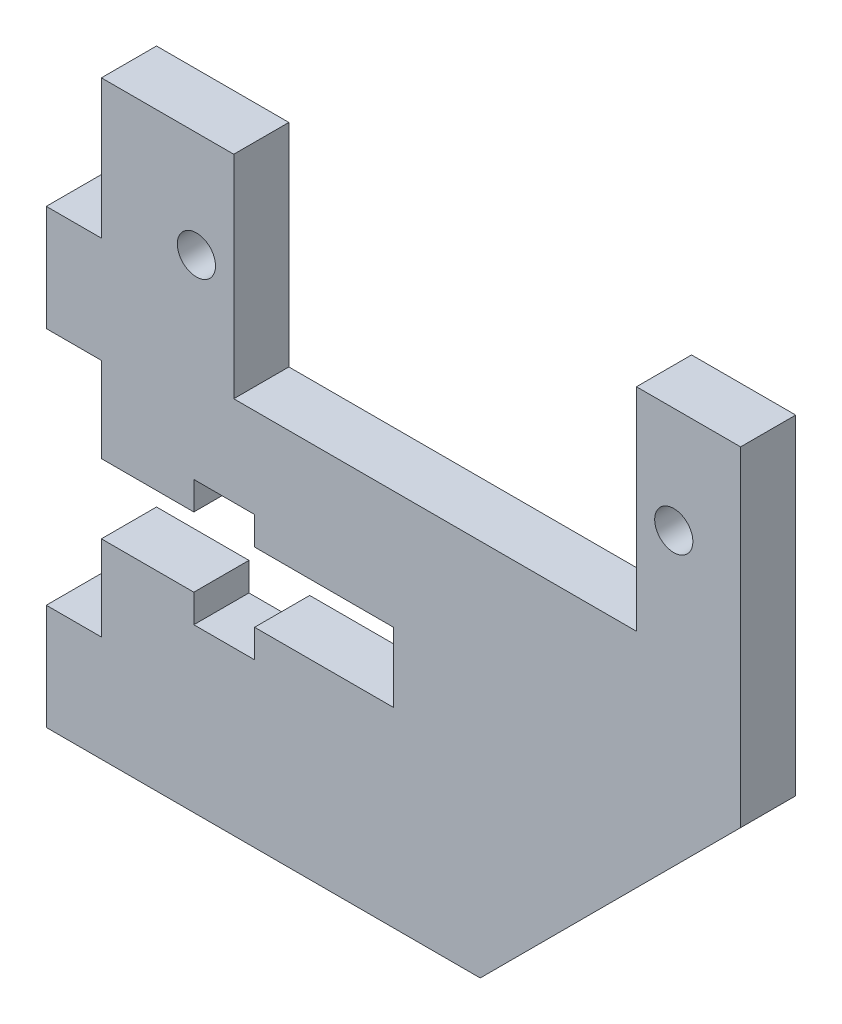
SolidWorks part; units mm, degrees
ref_plane "Front Plane" through (0, 0, 0) normal (0, 0, 1) x (1, 0, 0)
ref_plane "Top Plane" through (0, 0, 0) normal (0, 1, 0) x (1, 0, 0)
ref_plane "Right Plane" through (0, 0, 0) normal (1, 0, 0) x (0, 0, -1)
sketch "Sketch1" plane through (0, 0, 0) normal (0, 0, 1) x (1, 0, 0)
  line L0 (10.8, 34) -> (10.8, 21.8)
  line L1 (0, 0) -> (40, 0)
  line L2 (0, 0) -> (0, 6.1)
  line L3 (3.175, 34) -> (10.8, 34)
  line L4 (40, 0) -> (40, 34)
  line L5 (10.8, 21.8) -> (34, 21.8)
  line L6 (34, 21.8) -> (34, 34)
  line L7 (34, 34) -> (40, 34)
  line L8 (-11.825, 17) -> (40, 17) construction
  line L9 (0, 19.9) -> (3.175, 19.9)
  line L10 (12, 15) -> (20, 15)
  line L11 (0, 6.1) -> (3.175, 6.1)
  line L12 (3.175, 19.9) -> (3.175, 15)
  line L13 (3.175, 15) -> (8.5, 15)
  line L14 (8.5, 11) -> (8.5, 9.375)
  line L15 (3.175, 11) -> (8.5, 11)
  line L16 (20, 15) -> (20, 11)
  line L17 (8.5, 16.625) -> (12, 16.625)
  line L18 (8.5, 16.625) -> (8.5, 15)
  line L19 (8.5, 9.375) -> (12, 9.375)
  line L20 (12, 16.625) -> (12, 15)
  line L21 (3.175, 11) -> (3.175, 6.1)
  line L22 (12, 11) -> (12, 9.375)
  line L23 (0, 19.9) -> (0, 26)
  line L24 (12, 11) -> (20, 11)
  line L26 (0, 26) -> (3.175, 26)
  line L27 (0, 26) -> (0, 34)
  line L28 (0, 34) -> (3.175, 34)
  line L29 (3.175, 26) -> (3.175, 34)
  circle A0 centre (8.65, 27.9) radius 1.1
  circle A1 centre (36.15, 27.9) radius 1.1
  dimension "D8" = 2.2
  dimension "D9" = 2.2
  dimension "D1" = 34
  dimension "D2" = 40
  dimension "D3" = 12.2
  dimension "D4" = 23.2
  dimension "D5" = 6
  dimension "D6" = 27.5
  dimension "D7" = 6.1
  dimension "D10" = 2.15
  dimension "D11" = 19.9
  dimension "D12" = 6.1
  dimension "D13" = 3.175
  dimension "D14" = 4
  dimension "D15" = 7.25
  dimension "D16" = 15
  dimension "D17" = 16.625
  dimension "D18" = 3.5
  dimension "D19" = 20
  dimension "D20" = 8.5
  dimension "D21" = 6.1
  dimension "D22" = 3.175
extrude "Boss-Extrude1" add sketch "Sketch1" along normal blind 3.175 contours L12 L8 L4 L7 L6 L5 L0 L3 L29 L26 L23 L9 A0 A1 | L8 L12 L13 L18 L17 L20 L10 L16 L24 L22 L19 L14 L15 L21 L11 L2 L1 L4
chamfer "Chamfer1" distance 15 angle 45 1 edges at (40, 0, 1.5875)
